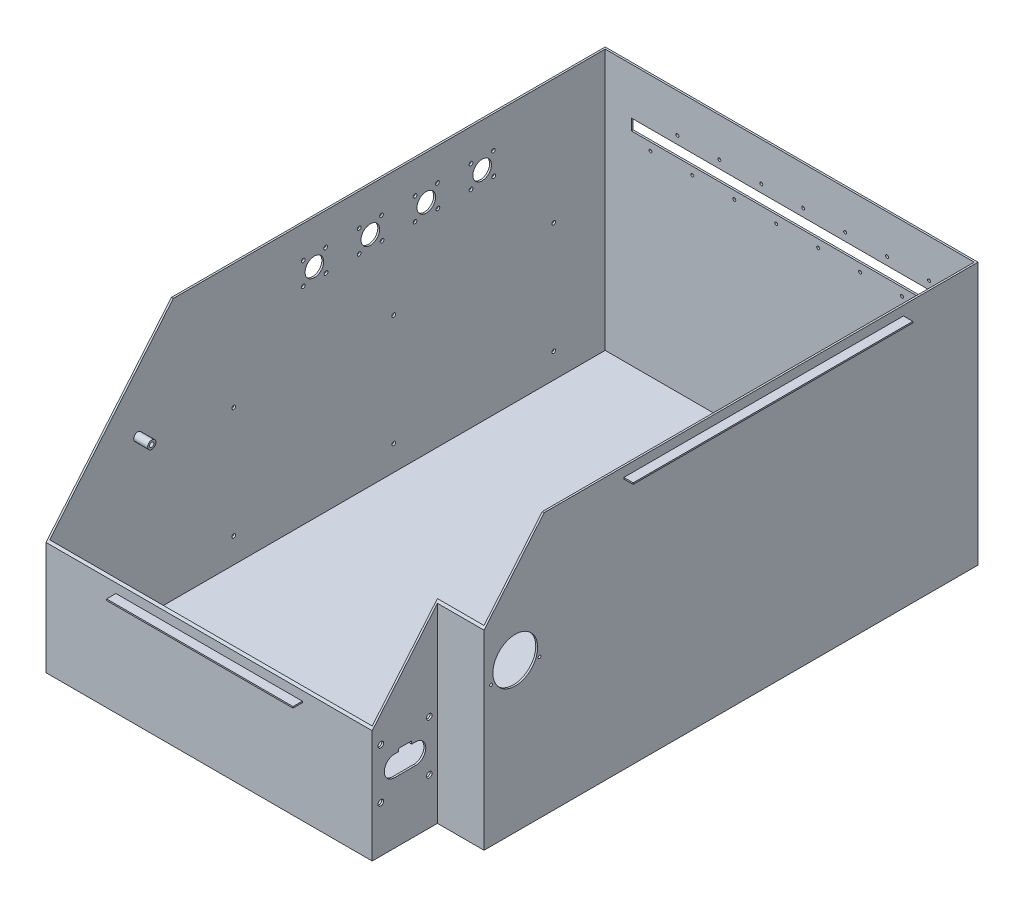
SolidWorks part; units mm, degrees
ref_plane "Front Plane" through (0, 0, 0) normal (0, 0, 1) x (1, 0, 0)
ref_plane "Top Plane" through (0, 0, 0) normal (0, 1, 0) x (1, 0, 0)
ref_plane "Right Plane" through (0, 0, 0) normal (1, 0, 0) x (0, 0, -1)
sketch "Sketch1" plane through (0, 0, 0) normal (0, 1, 0) x (1, 0, 0)
  line L1 (-200, 237.8263) -> (200, 237.8263)
  line L2 (-200, 237.8263) -> (-200, -362.1737)
  line L3 (-200, -362.1737) -> (150, -362.1737)
  line L4 (200, 237.8263) -> (200, -292.1737)
  line L6 (200, -292.1737) -> (150, -292.1737)
  line L7 (150, -292.1737) -> (150, -362.1737)
  line L8 (0, -55) -> (0, 55) construction
  point P1 (0, 237.8263)
  dimension "D1" = 600
  dimension "D2" = 400
  dimension "D5" = 70
  dimension "D6" = 50
extrude "Boss-Extrude1" add sketch "Sketch1" along normal blind 1.5
sketch "Sketch2" plane through (0, 1.5, 0) normal (0, 1, 0) x (1, 0, 0)
  line L60 (-198, 235.8263) -> (-198, -360.1737)
  line L61 (-198, -360.1737) -> (148, -360.1737)
  line L62 (148, -360.1737) -> (148, -290.1737)
  line L63 (148, -290.1737) -> (198, -290.1737)
  line L64 (198, -290.1737) -> (198, 235.8263)
  line L65 (198, 235.8263) -> (-198, 235.8263)
  line L66 (-200, 237.8263) -> (-200, -362.1737)
  line L67 (-200, -362.1737) -> (150, -362.1737)
  line L68 (150, -362.1737) -> (150, -292.1737)
  line L69 (150, -292.1737) -> (200, -292.1737)
  line L70 (200, -292.1737) -> (200, 237.8263)
  line L71 (200, 237.8263) -> (-200, 237.8263)
  line L72 (-200, 237.8263) -> (-200, -362.1737)
  line L73 (-200, -362.1737) -> (150, -362.1737)
  line L74 (150, -362.1737) -> (150, -292.1737)
  line L75 (150, -292.1737) -> (200, -292.1737)
  line L76 (200, -292.1737) -> (200, 237.8263)
  line L77 (200, 237.8263) -> (-200, 237.8263)
  dimension "D3" = 2
  dimension "D4" = 2
  dimension "D2" = 2
  dimension "D5" = 2
  dimension "D6" = 2
  dimension "D1" = 0
extrude "Boss-Extrude2" add sketch "Sketch2" along normal blind 280
sketch "Sketch3" plane through (-200, 0, 0) normal (-1, 0, 0) x (0, 0, 1)
  line L3 (362.1737, 281.5) -> (362.1737, 0) construction
  line L4 (362.1737, 121.1176) -> (227.5969, 281.5)
  line L6 (-237.8263, 281.5) -> (362.1737, 281.5) construction
  line L9 (362.1737, 281.5) -> (362.1737, 121.1176)
  line L10 (227.5969, 281.5) -> (362.1737, 281.5)
  dimension "D1" = 50
sketch "Sketch4" plane through (0, 0, -237.8263) normal (0, 0, -1) x (-1, 0, 0)
  line L0 (-200, 281.5) -> (-200, 0) construction
  line L1 (-200, 234.6761) -> (200, 234.6761)
  line L2 (-200, 234.6761) -> (-200, 192.2905)
  line L3 (-200, 192.2905) -> (200, 192.2905)
  line L4 (200, 234.6761) -> (200, 192.2905)
  line L5 (200, 281.5) -> (200, 0) construction
extrude "Boss-Extrude3" add sketch "Sketch4" against normal blind 2
extrude "Cut-Extrude1" cut sketch "Sketch3" against normal through all both and the other way through all
sketch "Sketch5" plane through (-200, 0, 0) normal (-1, 0, 0) x (0, 0, 1)
  line L0 (-115.8263, 223.1206) -> (-115.8263, 247.1206) construction
  line L5 (-115.8263, 223.1206) -> (-91.8263, 223.1206) construction
  line L6 (-115.8263, 247.1206) -> (-91.8263, 247.1206) construction
  line L7 (-91.8263, 223.1206) -> (-91.8263, 247.1206) construction
  line L8 (-115.8263, 223.1206) -> (-91.8263, 247.1206) construction
  line L9 (-115.8263, 247.1206) -> (-91.8263, 223.1206) construction
  line L10 (-55.8263, 223.1206) -> (-55.8263, 247.1206) construction
  line L11 (-55.8263, 223.1206) -> (-31.8263, 223.1206) construction
  line L12 (-55.8263, 247.1206) -> (-31.8263, 247.1206) construction
  line L13 (-31.8263, 223.1206) -> (-31.8263, 247.1206) construction
  line L14 (-55.8263, 223.1206) -> (-31.8263, 247.1206) construction
  line L15 (-55.8263, 247.1206) -> (-31.8263, 223.1206) construction
  line L16 (4.1737, 223.1206) -> (4.1737, 247.1206) construction
  line L17 (4.1737, 223.1206) -> (28.1737, 223.1206) construction
  line L18 (4.1737, 247.1206) -> (28.1737, 247.1206) construction
  line L19 (28.1737, 223.1206) -> (28.1737, 247.1206) construction
  line L20 (4.1737, 223.1206) -> (28.1737, 247.1206) construction
  line L21 (4.1737, 247.1206) -> (28.1737, 223.1206) construction
  line L22 (64.1737, 223.1206) -> (64.1737, 247.1206) construction
  line L23 (64.1737, 223.1206) -> (88.1737, 223.1206) construction
  line L24 (64.1737, 247.1206) -> (88.1737, 247.1206) construction
  line L25 (88.1737, 223.1206) -> (88.1737, 247.1206) construction
  line L26 (64.1737, 223.1206) -> (88.1737, 247.1206) construction
  line L27 (64.1737, 247.1206) -> (88.1737, 223.1206) construction
  line L28 (-235.8263, 281.5) -> (-235.8263, 1.5) construction
  circle A0 centre (-115.8263, 247.1206) radius 2
  circle A1 centre (-116.3263, 223.1259) radius 2
  circle A2 centre (-91.8263, 223.1206) radius 2
  circle A3 centre (-91.8263, 247.1206) radius 2
  circle A4 centre (-103.8263, 235.1206) radius 10
  circle A5 centre (-55.8263, 247.1206) radius 2
  circle A6 centre (-56.3263, 223.1259) radius 2
  circle A7 centre (-31.8263, 223.1206) radius 2
  circle A8 centre (-31.8263, 247.1206) radius 2
  circle A9 centre (-43.8263, 235.1206) radius 10
  circle A10 centre (4.1737, 247.1206) radius 2
  circle A11 centre (3.6737, 223.1259) radius 2
  circle A12 centre (28.1737, 223.1206) radius 2
  circle A13 centre (28.1737, 247.1206) radius 2
  circle A14 centre (16.1737, 235.1206) radius 10
  circle A15 centre (64.1737, 247.1206) radius 2
  circle A16 centre (63.6737, 223.1259) radius 2
  circle A17 centre (88.1737, 223.1206) radius 2
  circle A18 centre (88.1737, 247.1206) radius 2
  circle A19 centre (76.1737, 235.1206) radius 10
  point P9 (-103.8263, 235.1206)
  point P24 (-43.8263, 235.1206)
  point P38 (16.1737, 235.1206)
  point P52 (76.1737, 235.1206)
  dimension "D2" = 20
  dimension "D5" = 4
  dimension "D1" = 24
  dimension "D3" = 24
  dimension "D4" = 24
  dimension "D7" = 120
  dimension "D6" = 4
sketch "Sketch6" plane through (-198, 0, 0) normal (1, 0, 0) x (0, 0, -1)
  arc A0 (151.1392, 167.4539) -> (156.7272, 167.4539) centre (153.9332, 167.4539) ccw construction
  arc A1 (-68.8756, 167.4539) -> (-63.2876, 167.4539) centre (-66.0816, 167.4539) ccw construction
  arc A2 (-178.883, 167.4539) -> (-173.295, 167.4539) centre (-176.089, 167.4539) ccw construction
  arc A3 (151.1392, 167.4539) -> (156.7272, 167.4539) centre (153.9332, 167.4539) ccw
  arc A4 (-68.8756, 167.4539) -> (-63.2876, 167.4539) centre (-66.0816, 167.4539) ccw
  arc A5 (-178.883, 167.4539) -> (-173.295, 167.4539) centre (-176.089, 167.4539) ccw
  circle A6 centre (-176.089, 167.4539) radius 2.794
  circle A7 centre (-176.089, 167.4539) radius 4.5
  circle A8 centre (-64.4633, 167.4539) radius 4.5
  circle A9 centre (-64.4633, 167.4539) radius 2.794
  circle A10 centre (155.5515, 167.4539) radius 2.794
  circle A11 centre (155.5515, 167.4539) radius 4.5
  dimension "D1" = 9
extrude "Boss-Extrude4" [suppressed] add sketch "Sketch6" along normal blind 50 contours A4 A9 | A8 | A7 | A6 | A11 | A10
sketch "Sketch8" plane through (-198, 0, 0) normal (1, 0, 0) x (0, 0, -1)
  line L0 (235.8263, 1.5) -> (-360.1737, 1.5) construction
  line L1 (-360.1737, 123.5011) -> (-360.1737, 1.5) construction
  circle A0 centre (-265.6737, 172.1992) radius 2.39
  circle A1 centre (-265.6737, 172.1992) radius 4.39
  circle A2 centre (-265.1737, 16.5) radius 2.39
  circle A3 centre (-265.1737, 16.5) radius 4.39
  dimension "D3" = 4.78
  dimension "D4" = 2
  dimension "D1" = 155.7
  dimension "D2" = 15
  dimension "D5" = 95
extrude "Boss-Extrude5" add sketch "Sketch8" along normal blind 15
sketch "Sketch10" plane through (148, 0, 0) normal (-1, 0, 0) x (0, 0, 1)
  line L0 (315.6737, 86.5) -> (320.9237, 86.5) construction
  line L1 (315.6737, 66.5) -> (338.1737, 66.5) construction
  line L2 (338.1737, 76.5) -> (315.6737, 76.5) construction
  line L3 (360.1737, 1.5) -> (290.1737, 1.5) construction
  line L5 (320.9237, 86.5) -> (320.9237, 89.5) construction
  line L6 (320.9237, 89.5) -> (332.9237, 89.5) construction
  line L7 (332.9237, 86.5) -> (332.9237, 89.5) construction
  line L8 (360.1737, 123.5011) -> (360.1737, 1.5) construction
  line L9 (332.9237, 86.5) -> (338.1737, 86.5) construction
  line L10 (319.9237, 90.5) -> (333.9237, 90.5)
  line L11 (333.9237, 87.5) -> (333.9237, 90.5)
  line L12 (333.9237, 87.5) -> (338.1737, 87.5)
  line L13 (315.6737, 65.5) -> (338.1737, 65.5)
  line L14 (315.6737, 87.5) -> (319.9237, 87.5)
  line L15 (319.9237, 87.5) -> (319.9237, 90.5)
  line L17 (300.9737, 49.55) -> (352.8737, 49.55) construction
  line L18 (300.9737, 49.55) -> (300.9737, 103.45) construction
  line L19 (300.9737, 103.45) -> (352.8737, 103.45) construction
  line L20 (352.8737, 49.55) -> (352.8737, 103.45) construction
  line L21 (300.9737, 49.55) -> (352.8737, 103.45) construction
  line L22 (300.9737, 103.45) -> (352.8737, 49.55) construction
  arc A0 (315.6737, 86.5) -> (315.6737, 66.5) centre (315.6737, 76.5) ccw construction
  arc A1 (338.1737, 66.5) -> (338.1737, 86.5) centre (338.1737, 76.5) ccw construction
  arc A2 (338.1737, 65.5) -> (338.1737, 87.5) centre (338.1737, 76.5) ccw
  arc A3 (315.6737, 87.5) -> (315.6737, 65.5) centre (315.6737, 76.5) ccw
  circle A4 centre (300.9737, 103.45) radius 3
  circle A5 centre (352.8737, 103.45) radius 3
  circle A6 centre (300.9737, 49.55) radius 3
  circle A7 centre (352.8737, 49.55) radius 3
  point P12 (326.9237, 89.5)
  point P13 (326.9237, 76.5)
  point P26 (326.9237, 76.5)
  dimension "D1" = 65
  dimension "D2" = 22.5
  dimension "D6" = 20
  dimension "D10" = 6
  dimension "D3" = 22
  dimension "D4" = 12
  dimension "D5" = 3
  dimension "D8" = 51.9
  dimension "D9" = 53.9
  dimension "D7" = 1
extrude "Cut-Extrude2" cut sketch "Sketch10" against normal up to surface (2 mm away)
sketch "Sketch11" plane through (148, 0, 0) normal (-1, 0, 0) x (0, 0, 1)
  line L0 (298.4737, 103.43) -> (298.4737, 49.53) construction
  line L13 (315.6737, 66.5) -> (338.1737, 66.5) construction
  line L14 (315.6737, 86.5) -> (320.9237, 86.5) construction
  line L15 (315.6737, 66.5) -> (338.1737, 66.5)
  line L19 (315.6737, 86.5) -> (318.4237, 86.5)
  line L20 (333.9237, 90.5) -> (319.9237, 90.5)
  line L21 (333.9237, 90.5) -> (319.9237, 90.5)
  line L22 (333.9237, 87.5) -> (333.9237, 90.5)
  line L23 (333.9237, 87.5) -> (333.9237, 90.5)
  line L28 (330.4237, 86.5) -> (320.9237, 86.5)
  line L29 (315.7815, 66) -> (338.2021, 66)
  line L30 (330.9237, 86) -> (320.2852, 86)
  line L31 (330.9237, 86) -> (330.9237, 91)
  line L32 (330.9237, 91) -> (317.9237, 91)
  line L33 (317.9237, 91) -> (317.9237, 87)
  line L34 (315.7815, 87) -> (317.9237, 87)
  line L36 (298.4737, 103.43) -> (350.3737, 103.43) construction
  line L43 (333.9237, 90.5) -> (319.9237, 90.5)
  line L44 (333.9237, 90.5) -> (319.9237, 90.5)
  line L45 (333.9237, 87.5) -> (333.9237, 90.5)
  line L46 (333.9237, 87.5) -> (333.9237, 90.5)
  line L47 (338.1737, 87.5) -> (333.9237, 87.5)
  line L48 (338.1737, 87.5) -> (333.9237, 87.5)
  line L49 (315.6737, 65.5) -> (338.1737, 65.5)
  line L50 (315.6737, 65.5) -> (338.1737, 65.5)
  line L51 (319.9237, 87.5) -> (315.6737, 87.5)
  line L52 (319.9237, 87.5) -> (315.6737, 87.5)
  line L53 (319.9237, 90.5) -> (319.9237, 87.5)
  line L54 (319.9237, 90.5) -> (319.9237, 87.5)
  line L55 (333.9237, 90.5) -> (319.9237, 90.5)
  line L56 (333.9237, 90.5) -> (319.9237, 90.5)
  line L57 (333.9237, 87.5) -> (333.9237, 90.5)
  line L58 (333.9237, 87.5) -> (333.9237, 90.5)
  line L59 (338.1737, 87.5) -> (333.9237, 87.5)
  line L60 (338.1737, 87.5) -> (333.9237, 87.5)
  line L61 (315.6737, 65.5) -> (338.1737, 65.5)
  line L62 (315.6737, 65.5) -> (338.1737, 65.5)
  line L63 (319.9237, 87.5) -> (315.6737, 87.5)
  line L64 (319.9237, 87.5) -> (315.6737, 87.5)
  line L65 (319.9237, 90.5) -> (319.9237, 87.5)
  line L66 (319.9237, 90.5) -> (319.9237, 87.5)
  line L67 (330.4237, 86.5) -> (330.4237, 90.5) construction
  line L68 (330.4237, 90.5) -> (318.4237, 90.5) construction
  line L69 (318.4237, 90.5) -> (318.4237, 86.5) construction
  line L70 (338.1737, 87.5) -> (333.9237, 87.5)
  line L71 (338.1737, 87.5) -> (333.9237, 87.5)
  line L72 (315.6737, 65.5) -> (338.1737, 65.5)
  line L73 (315.6737, 65.5) -> (338.1737, 65.5)
  line L74 (319.9237, 87.5) -> (315.6737, 87.5)
  line L75 (319.9237, 87.5) -> (315.6737, 87.5)
  line L76 (319.9237, 90.5) -> (319.9237, 87.5)
  line L77 (319.9237, 90.5) -> (319.9237, 87.5)
  arc A4 (338.2021, 66) -> (320.2852, 86) centre (336.3485, 82.3648) ccw
  arc A5 (338.1737, 65.5) -> (338.1737, 87.5) centre (338.1737, 76.5) ccw
  arc A7 (338.1737, 65.5) -> (338.1737, 87.5) centre (338.1737, 76.5) ccw
  arc A9 (315.7815, 87) -> (315.7815, 66) centre (311.0911, 76.5) ccw
  circle A10 centre (298.4737, 103.43) radius 3
  circle A11 centre (298.4737, 49.53) radius 3
  circle A12 centre (350.3737, 103.43) radius 3
  circle A13 centre (350.3737, 49.53) radius 3
  arc A16 (338.1737, 66.5) -> (320.9237, 86.5) centre (336.3485, 82.3648) ccw construction
  arc A17 (338.1737, 65.5) -> (338.1737, 87.5) centre (338.1737, 76.5) ccw
  arc A18 (315.6737, 87.5) -> (315.6737, 65.5) centre (315.6737, 76.5) ccw
  arc A19 (315.6737, 87.5) -> (315.6737, 65.5) centre (315.6737, 76.5) ccw
  arc A20 (315.6737, 86.5) -> (315.6737, 66.5) centre (311.0911, 76.5) ccw construction
  arc A21 (338.1737, 65.5) -> (338.1737, 87.5) centre (338.1737, 76.5) ccw
  arc A22 (315.6737, 87.5) -> (315.6737, 65.5) centre (315.6737, 76.5) ccw
  arc A23 (315.6737, 87.5) -> (315.6737, 65.5) centre (315.6737, 76.5) ccw
  arc A24 (338.1737, 65.5) -> (338.1737, 87.5) centre (338.1737, 76.5) ccw
  arc A25 (338.1737, 65.5) -> (338.1737, 87.5) centre (338.1737, 76.5) ccw
  arc A26 (315.6737, 87.5) -> (315.6737, 65.5) centre (315.6737, 76.5) ccw
  arc A27 (315.6737, 87.5) -> (315.6737, 65.5) centre (315.6737, 76.5) ccw
  dimension "D5" = 6
  dimension "D6" = 51.9
  dimension "D7" = 53.9
  dimension "D1" = 0
  dimension "D2" = 0
  dimension "D3" = 0
  dimension "D4" = 0.5
extrude "Cut-Extrude3" [suppressed] cut sketch "Sketch11" against normal through all
sketch "Sketch14" plane through (148, 0, 0) normal (-1, 0, 0) x (0, 0, 1)
  line L0 (362.1737, 121.1176) -> (362.1737, 0) construction
  line L1 (362.1737, 0) -> (292.1737, 0) construction
  circle A0 centre (297.2737, 103.43) radius 3
  circle A1 centre (349.1737, 103.43) radius 3
  circle A2 centre (349.1737, 49.53) radius 3
  circle A3 centre (297.2737, 49.53) radius 3
  dimension "D5" = 6
  dimension "D1" = 51.9
  dimension "D2" = 53.9
  dimension "D3" = 13
  dimension "D4" = 103.43
extrude "Cut-Extrude4" [suppressed] cut sketch "Sketch14" against normal up to surface (1.5 mm away)
sketch "Sketch15" plane through (198, 0, 0) normal (-1, 0, 0) x (0, 0, 1)
  line L1 (-223.8263, 252.1363) -> (-208.8263, 252.1363)
  line L2 (-223.8263, 252.1363) -> (-223.8263, 250.6363)
  line L3 (-223.8263, 250.6363) -> (-208.8263, 250.6363)
  line L4 (-208.8263, 252.1363) -> (-208.8263, 250.6363)
  line L5 (-235.8263, 281.5) -> (-235.8263, 1.5) construction
  line L6 (196.1737, 252.1363) -> (211.1737, 252.1363)
  line L7 (196.1737, 250.6363) -> (211.1737, 250.6363)
  line L8 (196.1737, 252.1363) -> (196.1737, 250.6363)
  line L9 (211.1737, 252.1363) -> (211.1737, 250.6363)
  dimension "D1" = 1.5
  dimension "D2" = 15
  dimension "D3" = 12
  dimension "D4" = 432
  dimension "D5" = 15
extrude "Boss-Extrude6" [suppressed] add sketch "Sketch15" along normal blind 15
ref_plane "Plane1" [suppressed] through (0, 0, -203.8263) normal (0, 0, -1) x (-1, 0, 0)
sketch "Sketch17" [suppressed] plane through (0, 0, -208.8263) normal (0, 0, 1) x (1, 0, 0)
  line L0 (198, 250.6363) -> (198, 235.6363)
  line L1 (198, 281.5) -> (198, 207.307) construction
  line L2 (198, 235.6363) -> (183, 250.6363)
  line L3 (183, 250.6363) -> (198, 250.6363)
  dimension "D1" = 15
extrude "Boss-Extrude7" [suppressed] add sketch "Sketch17" against normal blind 1.5
ref_plane "Plane2" [suppressed] through (0, 0, 191.1737) normal (0, 0, 1) x (1, 0, 0)
sketch "Sketch18" [suppressed] plane through (0, 0, 196.1737) normal (0, 0, 1) x (1, 0, 0)
  line L0 (198, 250.6363) -> (198, 235.6363)
  line L1 (198, 281.5) -> (198, 207.307) construction
  line L2 (198, 235.6363) -> (183, 250.6363)
  line L3 (183, 250.6363) -> (198, 250.6363)
  dimension "D1" = 15
extrude "Boss-Extrude8" [suppressed] add sketch "Sketch18" along normal blind 1.5
sketch "Sketch20" [suppressed] plane through (0, 252.1363, 0) normal (0, 1, 0) x (1, 0, 0)
  line L1 (183, 223.8263) -> (198, 223.8263) construction
  line L2 (183, 208.8263) -> (183, 223.8263) construction
  line L3 (183, -211.1737) -> (198, -211.1737) construction
  line L4 (183, -211.1737) -> (183, -196.1737) construction
  circle A0 centre (190.5, 216.3263) radius 2.4159
  circle A1 centre (190.5, -203.6737) radius 2
  dimension "D3" = 4
  dimension "D1" = 7.5
  dimension "D2" = 7.5
  dimension "D4" = 7.5
  dimension "D5" = 7.5
extrude "Cut-Extrude5" [suppressed] cut sketch "Sketch20" against normal up to surface (1.5 mm away)
extrude "Cut-Extrude7" cut sketch "Sketch5" against normal up to surface (2 mm away) up to face at (-198, 16.5, 260.7837)
sketch "Sketch21" plane through (0, 0, -237.8263) normal (0, 0, -1) x (-1, 0, 0)
  line L0 (-200, 281.5) -> (200, 281.5) construction
  line L1 (-150, 271.5) -> (150, 271.5)
  line L2 (-150, 271.5) -> (-150, 270)
  line L3 (-150, 270) -> (150, 270)
  line L4 (150, 271.5) -> (150, 270)
  point P6 (0, 281.5)
  point P7 (0, 271.5)
  dimension "D1" = 1.5
  dimension "D2" = 300
  dimension "D3" = 10
extrude "Boss-Extrude9" add sketch "Sketch21" along normal blind 10
sketch "Sketch22" plane through (-200, 0, 0) normal (-1, 0, 0) x (0, 0, 1)
  line L0 (-237.8263, 281.5) -> (227.5969, 281.5) construction
  line L1 (-157.8263, 271.5) -> (142.1737, 271.5)
  line L2 (-157.8263, 271.5) -> (-157.8263, 270)
  line L3 (-157.8263, 270) -> (142.1737, 270)
  line L4 (142.1737, 271.5) -> (142.1737, 270)
  line L5 (-237.8263, 281.5) -> (-237.8263, 0) construction
  dimension "D1" = 1.5
  dimension "D2" = 10
  dimension "D3" = 80
  dimension "D4" = 300
extrude "Boss-Extrude10" add sketch "Sketch22" along normal blind 10
ref_plane "Plane3" through (0, 0, -77.8263) normal (0, 0, -1) x (-1, 0, 0)
sketch "Sketch23" plane through (0, 0, -77.8263) normal (0, 0, -1) x (-1, 0, 0)
  line L0 (210, 270) -> (200, 270) construction
  line L1 (210, 270) -> (200, 270)
  line L2 (210, 270) -> (200, 260)
  line L3 (200, 281.5) -> (200, 0) construction
  line L4 (200, 260) -> (200, 270)
  dimension "D1" = 10
extrude "Boss-Extrude11" add sketch "Sketch23" along normal mid plane 1.5
ref_plane "Plane4" through (0, 0, 52.1737) normal (0, 0, 1) x (1, 0, 0)
sketch "Sketch24" plane through (0, 0, 52.1737) normal (0, 0, 1) x (1, 0, 0)
  line L6 (-210, 270) -> (-200, 260)
  line L7 (-200, 260) -> (-200, 270)
  line L8 (-200, 270) -> (-210, 270)
  line L9 (-210, 270) -> (-200, 260)
  line L10 (-200, 260) -> (-200, 270)
  line L11 (-200, 270) -> (-210, 270)
  dimension "D1" = 0
extrude "Boss-Extrude12" add sketch "Sketch24" along normal mid plane 1.5
ref_plane "Plane5" through (100, 0, 0) normal (1, 0, 0) x (0, 0, -1)
sketch "Sketch25" plane through (100, 0, 0) normal (1, 0, 0) x (0, 0, -1)
  line L0 (247.8263, 270) -> (237.8263, 270)
  line L1 (237.8263, 270) -> (237.8263, 260)
  line L2 (237.8263, 281.5) -> (237.8263, 0) construction
  line L3 (237.8263, 260) -> (247.8263, 270)
  dimension "D1" = 10
extrude "Boss-Extrude13" add sketch "Sketch25" along normal mid plane 1.5
ref_plane "Plane6" through (-100, 0, 0) normal (-1, 0, 0) x (0, 0, 1)
sketch "Sketch26" plane through (-100, 0, 0) normal (-1, 0, 0) x (0, 0, 1)
  line L3 (-247.8263, 270) -> (-237.8263, 260)
  line L4 (-237.8263, 260) -> (-237.8263, 270)
  line L5 (-237.8263, 270) -> (-247.8263, 270)
  line L6 (-247.8263, 270) -> (-237.8263, 260)
  line L7 (-237.8263, 260) -> (-237.8263, 270)
  line L8 (-237.8263, 270) -> (-247.8263, 270)
  dimension "D1" = 0
extrude "Boss-Extrude14" add sketch "Sketch26" along normal mid plane 1.5
mirror "Mirror1" about plane through (0, 0, 0) normal (1, 0, 0) of "Boss-Extrude11", "Boss-Extrude12", "Boss-Extrude10"
sketch "Sketch27" plane through (0, 0, 362.1737) normal (0, 0, 1) x (1, 0, 0)
  line L0 (150, 121.1176) -> (-200, 121.1176) construction
  line L1 (-125, 111.1176) -> (75, 111.1176)
  line L2 (-125, 111.1176) -> (-125, 109.6176)
  line L3 (-125, 109.6176) -> (75, 109.6176)
  line L4 (75, 111.1176) -> (75, 109.6176)
  line L5 (150, 121.1176) -> (-200, 121.1176) construction
  point P6 (-25, 121.1176)
  point P7 (-25, 111.1176)
  dimension "D1" = 1.5
  dimension "D2" = 200
  dimension "D3" = 10
extrude "Boss-Extrude15" add sketch "Sketch27" along normal blind 10
ref_plane "Plane7" through (-95, 0, 0) normal (-1, 0, 0) x (0, 0, 1)
sketch "Sketch28" plane through (-95, 0, 0) normal (-1, 0, 0) x (0, 0, 1)
  line L0 (372.1737, 109.6176) -> (362.1737, 109.6176)
  line L1 (362.1737, 109.6176) -> (362.1737, 99.6176)
  line L2 (362.1737, 121.1176) -> (362.1737, 0) construction
  line L3 (362.1737, 99.6176) -> (372.1737, 109.6176)
  dimension "D1" = 10
extrude "Boss-Extrude16" add sketch "Sketch28" along normal mid plane 1.5
ref_plane "Plane8" through (45, 0, 0) normal (1, 0, 0) x (0, 0, -1)
sketch "Sketch29" plane through (45, 0, 0) normal (1, 0, 0) x (0, 0, -1)
  line L3 (-372.1737, 109.6176) -> (-362.1737, 99.6176)
  line L4 (-362.1737, 99.6176) -> (-362.1737, 109.6176)
  line L5 (-362.1737, 109.6176) -> (-372.1737, 109.6176)
  line L6 (-372.1737, 109.6176) -> (-362.1737, 99.6176)
  line L7 (-362.1737, 99.6176) -> (-362.1737, 109.6176)
  line L8 (-362.1737, 109.6176) -> (-372.1737, 109.6176)
  dimension "D1" = 0
extrude "Boss-Extrude17" add sketch "Sketch29" along normal mid plane 1.5
sketch "Sketch30" plane through (200, 0, 0) normal (1, 0, 0) x (0, 0, -1)
  line L1 (-292.1737, 0) -> (237.8263, 0) construction
  line L2 (-292.1737, 204.5403) -> (-292.1737, 0) construction
  circle A0 centre (-258.6737, 160) radius 24
  circle A1 centre (-284.6737, 150) radius 1.5
  circle A2 centre (-232.6737, 150) radius 1.5
  dimension "D1" = 48
  dimension "D2" = 3
  dimension "D3" = 3
  dimension "D4" = 26
  dimension "D5" = 10
  dimension "D6" = 26
  dimension "D7" = 10
  dimension "D8" = 160
  dimension "D9" = 33.5
extrude "Cut-Extrude8" cut sketch "Sketch30" against normal up to surface (2 mm away) up to face at (198, 154.5848, 67.2583)
sketch "Sketch33" plane through (-200, 0, 0) normal (-1, 0, 0) x (0, 0, 1)
  line L0 (-237.8263, 281.5) -> (-237.8263, 0) construction
  line L1 (-237.8263, 0) -> (362.1737, 0) construction
  circle A0 centre (-180.6263, 147.77) radius 2
  circle A1 centre (-180.6263, 28.39) radius 2
  circle A2 centre (-8.9263, 147.77) radius 2
  circle A3 centre (-8.9263, 28.39) radius 2
  circle A4 centre (162.7737, 147.77) radius 2
  circle A5 centre (162.7737, 28.39) radius 2
  dimension "D3" = 4
  dimension "D1" = 57.2
  dimension "D2" = 119.38
  dimension "D4" = 28.39
  dimension "D5" = 3
extrude "Cut-Extrude9" cut sketch "Sketch33" against normal up to surface (2 mm away) up to face at (-198, 223.1206, 26.1737)
sketch "Sketch42" plane through (0, 0, -235.8263) normal (0, 0, 1) x (1, 0, 0)
  line L8 (200, 281.5) -> (-200, 281.5) construction
  line L9 (170, 219.5) -> (-170, 219.5)
  line L10 (170, 219.5) -> (170, 231.5)
  line L11 (170, 231.5) -> (-170, 231.5)
  line L12 (-170, 219.5) -> (-170, 231.5)
  line L15 (200, 225.5) -> (-200, 225.5) construction
  line L16 (200, 281.5) -> (200, 0) construction
  line L17 (-200, 281.5) -> (-200, 0) construction
  line L18 (-72.5, 243) -> (-107.5, 243)
  line L19 (-117.5, 208) -> (-152.5, 208) construction
  line L20 (-117.5, 208) -> (-117.5, 243) construction
  line L21 (-117.5, 243) -> (-152.5, 243) construction
  line L22 (-152.5, 208) -> (-152.5, 243) construction
  line L25 (-72.5, 208) -> (-72.5, 243)
  line L26 (-107.5, 208) -> (-107.5, 243)
  line L27 (-72.5, 208) -> (-107.5, 208)
  line L29 (-27.5, 243) -> (-62.5, 243)
  line L30 (-27.5, 208) -> (-27.5, 243)
  line L31 (-62.5, 208) -> (-62.5, 243)
  line L32 (-27.5, 208) -> (-62.5, 208)
  line L34 (17.5, 243) -> (-17.5, 243)
  line L35 (17.5, 208) -> (17.5, 243)
  line L36 (-17.5, 208) -> (-17.5, 243)
  line L37 (17.5, 208) -> (-17.5, 208)
  line L39 (62.5, 243) -> (27.5, 243)
  line L40 (62.5, 208) -> (62.5, 243)
  line L41 (27.5, 208) -> (27.5, 243)
  line L42 (62.5, 208) -> (27.5, 208)
  line L44 (107.5, 243) -> (72.5, 243)
  line L45 (107.5, 208) -> (107.5, 243)
  line L46 (72.5, 208) -> (72.5, 243)
  line L47 (107.5, 208) -> (72.5, 208)
  line L49 (152.5, 243) -> (117.5, 243)
  line L50 (152.5, 208) -> (152.5, 243)
  line L51 (117.5, 208) -> (117.5, 243)
  line L52 (152.5, 208) -> (117.5, 208)
  circle A0 centre (-120.5, 240) radius 1.6
  circle A1 centre (-149.5, 211) radius 1.6
  circle A2 centre (-75.5, 240) radius 1.6
  circle A3 centre (-104.5, 211) radius 1.6
  circle A4 centre (-30.5, 240) radius 1.6
  circle A5 centre (-59.5, 211) radius 1.6
  circle A6 centre (14.5, 240) radius 1.6
  circle A7 centre (-14.5, 211) radius 1.6
  circle A8 centre (59.5, 240) radius 1.6
  circle A9 centre (30.5, 211) radius 1.6
  circle A10 centre (104.5, 240) radius 1.6
  circle A11 centre (75.5, 211) radius 1.6
  circle A12 centre (149.5, 240) radius 1.6
  circle A13 centre (120.5, 211) radius 1.6
  point P0 (0, 225.5)
  point P13 (-135, 225.5)
  point P72 (-152.5, 210.8199)
  dimension "D4" = 3
  dimension "D6" = 3
  dimension "D1" = 50
  dimension "D2" = 17.5
  dimension "D5" = 3
  dimension "D7" = 3
  dimension "D3" = 7
extrude "Cut-Extrude13" cut sketch "Sketch42" against normal blind 40
sketch "Sketch43" plane through (0, 0, 0) normal (0, -1, 0) x (1, 0, 0)
  line L0 (-200, 362.1737) -> (150, 362.1737) construction
  line L1 (150, 292.1737) -> (200, 292.1737)
  line L2 (150, 292.1737) -> (150, 362.1737)
  line L3 (150, 362.1737) -> (200, 362.1737)
  line L4 (200, 292.1737) -> (200, 362.1737)
  line L5 (200, 292.1737) -> (200, -237.8263) construction
